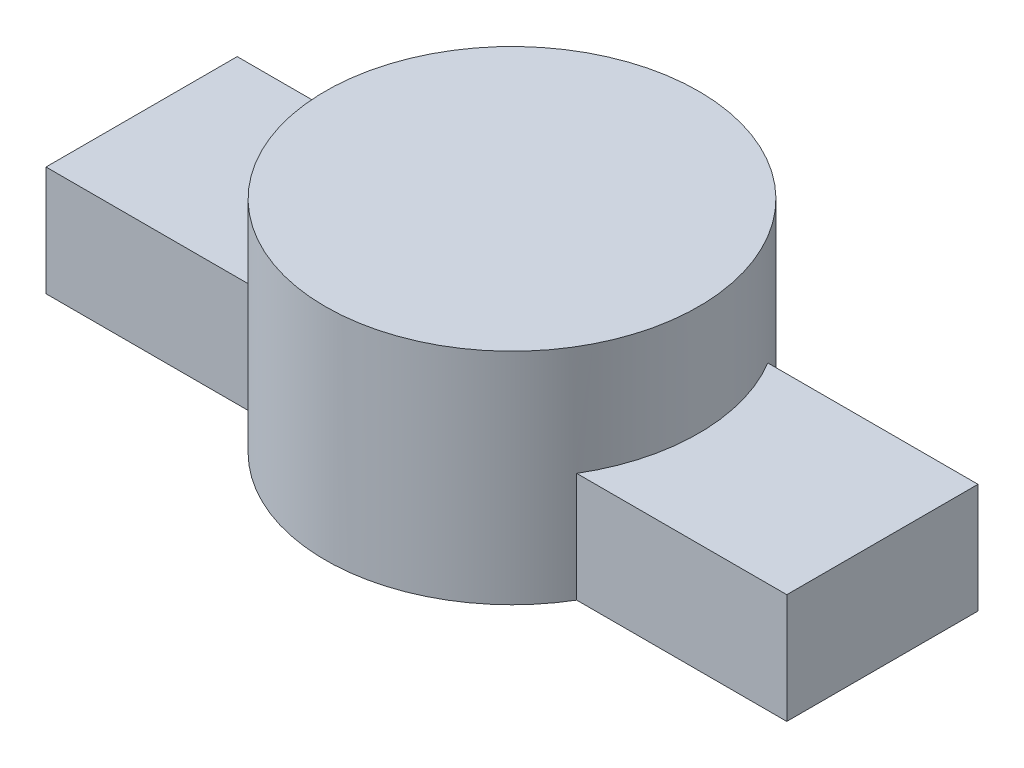
SolidWorks part; units mm, degrees
ref_plane "Front Plane" through (0, 0, 0) normal (0, 0, 1) x (1, 0, 0)
ref_plane "Top Plane" through (0, 0, 0) normal (0, 1, 0) x (1, 0, 0)
ref_plane "Right Plane" through (0, 0, 0) normal (1, 0, 0) x (0, 0, -1)
sketch "Sketch1" plane through (0, 0, 0) normal (0, 1, 0) x (1, 0, 0)
  circle A0 centre (0, 0) radius 8.5
  dimension "D1" = 17
extrude "Boss-Extrude1" add sketch "Sketch1" along normal blind 10
sketch "Sketch3" plane through (0, 0, 0) normal (0, -1, 0) x (1, 0, 0)
  line L1 (-16.8692, 4.354) -> (16.8692, 4.354)
  line L2 (-16.8692, 4.354) -> (-16.8692, -4.354)
  line L3 (-16.8692, -4.354) -> (16.8692, -4.354)
  line L4 (16.8692, 4.354) -> (16.8692, -4.354)
  line L5 (-16.8692, 4.354) -> (16.8692, -4.354) construction
  line L6 (-16.8692, -4.354) -> (16.8692, 4.354) construction
  point P0 (0, 0)
extrude "Boss-Extrude2" add sketch "Sketch3" against normal blind 5
